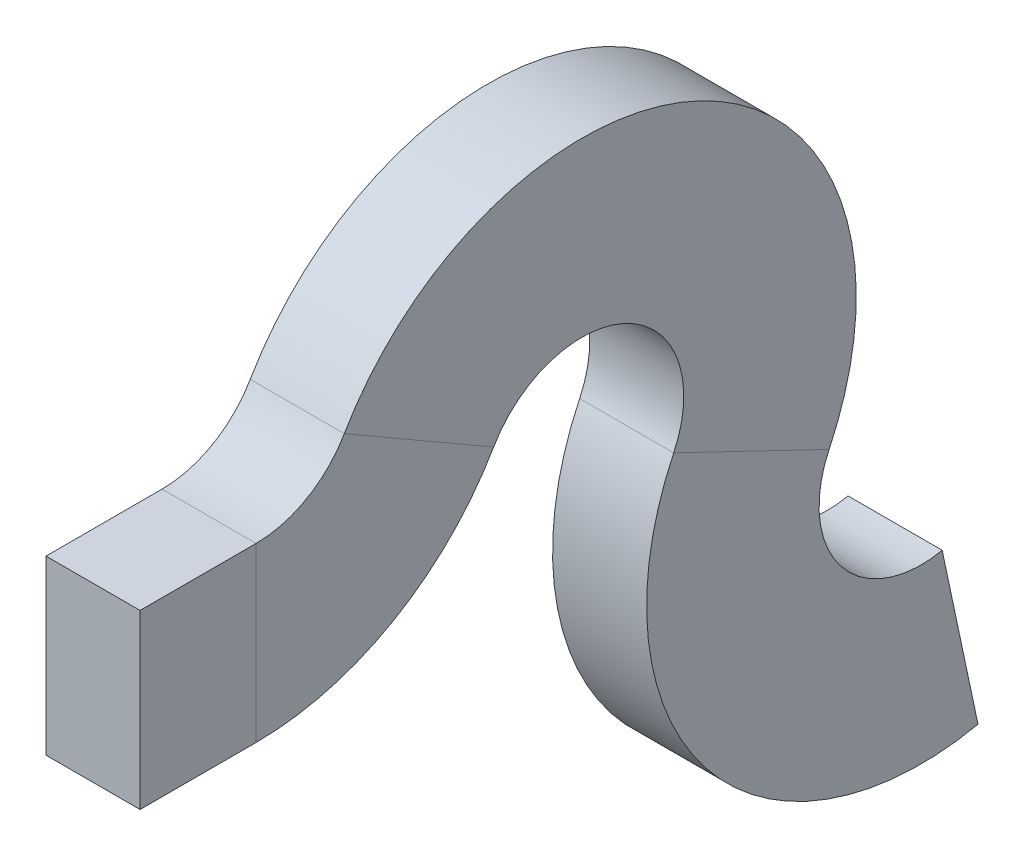
SolidWorks part; units mm, degrees
material "Латунь"
ref_plane "Спереди" through (0, 0, 0) normal (0, 0, 1) x (1, 0, 0)
ref_plane "Сверху" through (0, 0, 0) normal (0, 1, 0) x (1, 0, 0)
ref_plane "Справа" through (0, 0, 0) normal (1, 0, 0) x (0, 0, -1)
sketch "Эскиз сечения" plane through (0, 0, 0) normal (0, 0, 1) x (1, 0, 0)
  line L1 (-15, -27.5) -> (15, -27.5)
  line L2 (-15, -27.5) -> (-15, 27.5)
  line L3 (-15, 27.5) -> (15, 27.5)
  line L4 (15, -27.5) -> (15, 27.5)
  line L5 (-15, -27.5) -> (15, 27.5) construction
  line L6 (-15, 27.5) -> (15, -27.5) construction
  point P0 (0, 0)
  dimension "D1" = 55
  dimension "D2" = 30
sketch "Эскиз направляющей" plane through (0, 0, 0) normal (1, 0, 0) x (0, 0, -1)
  line L0 (0, 0) -> (37, 0)
  line L1 (249.0711, -52) -> (261.5458, -110.6889) construction
  arc A0 (37, 0) -> (88.9615, 30) centre (37, 60) ccw
  arc A1 (88.9615, 30) -> (194.9971, -26) centre (140.923, 0) cw
  arc A2 (194.9971, -26) -> (261.5458, -110.6889) centre (249.0711, -52) ccw
  dimension "D1" = 60
  dimension "D2" = 37
  dimension "D3" = 52
  dimension "D4" = 12
sweep "По траектории2" add profiles "Эскиз сечения" path "Эскиз направляющей"
